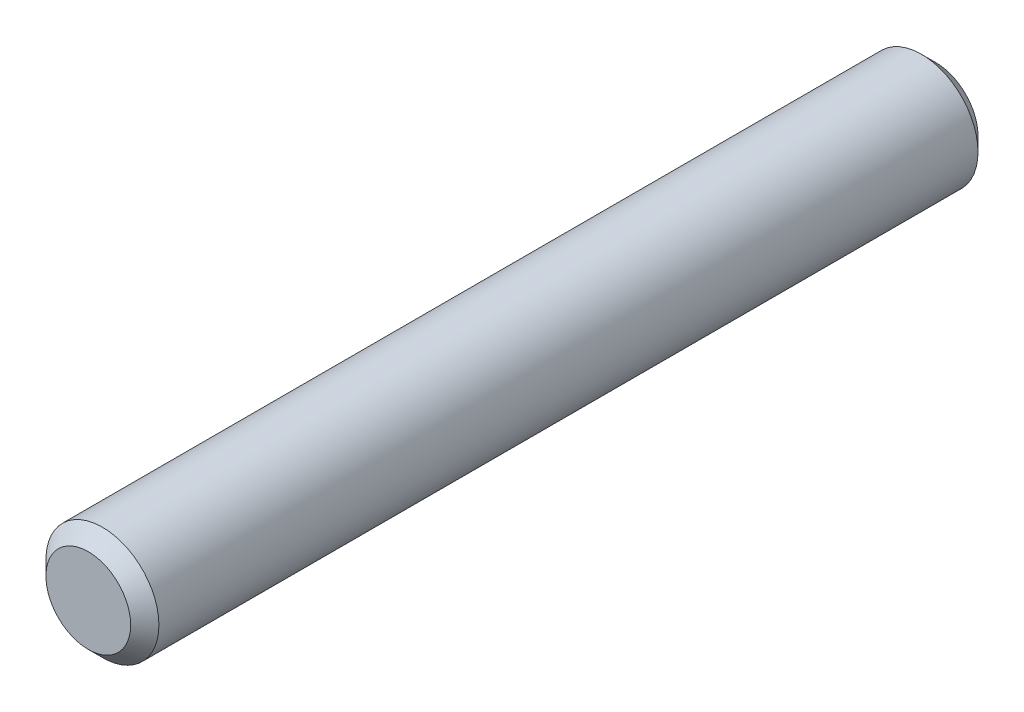
SolidWorks part; units mm, degrees
ref_plane "Front Plane" through (0, 0, 0) normal (0, 0, 1) x (1, 0, 0)
ref_plane "Top Plane" through (0, 0, 0) normal (0, 1, 0) x (1, 0, 0)
ref_plane "Right Plane" through (0, 0, 0) normal (1, 0, 0) x (0, 0, -1)
sketch "Sketch1" plane through (0, 0, 0) normal (0, 0, 1) x (1, 0, 0)
  circle A0 centre (0, 0) radius 2
  dimension "D1" = 4
extrude "Boss-Extrude1" add sketch "Sketch1" along normal blind 30
chamfer "Chamfer1" distance 0.5 angle 45 1 edges at (2, 0, 0)
ref_plane "Plane1" through (0, 0, 15) normal (0, 0, 1) x (1, 0, 0)
chamfer "Chamfer2" distance 0.5 angle 45 1 edges at (2, 0, 30)
